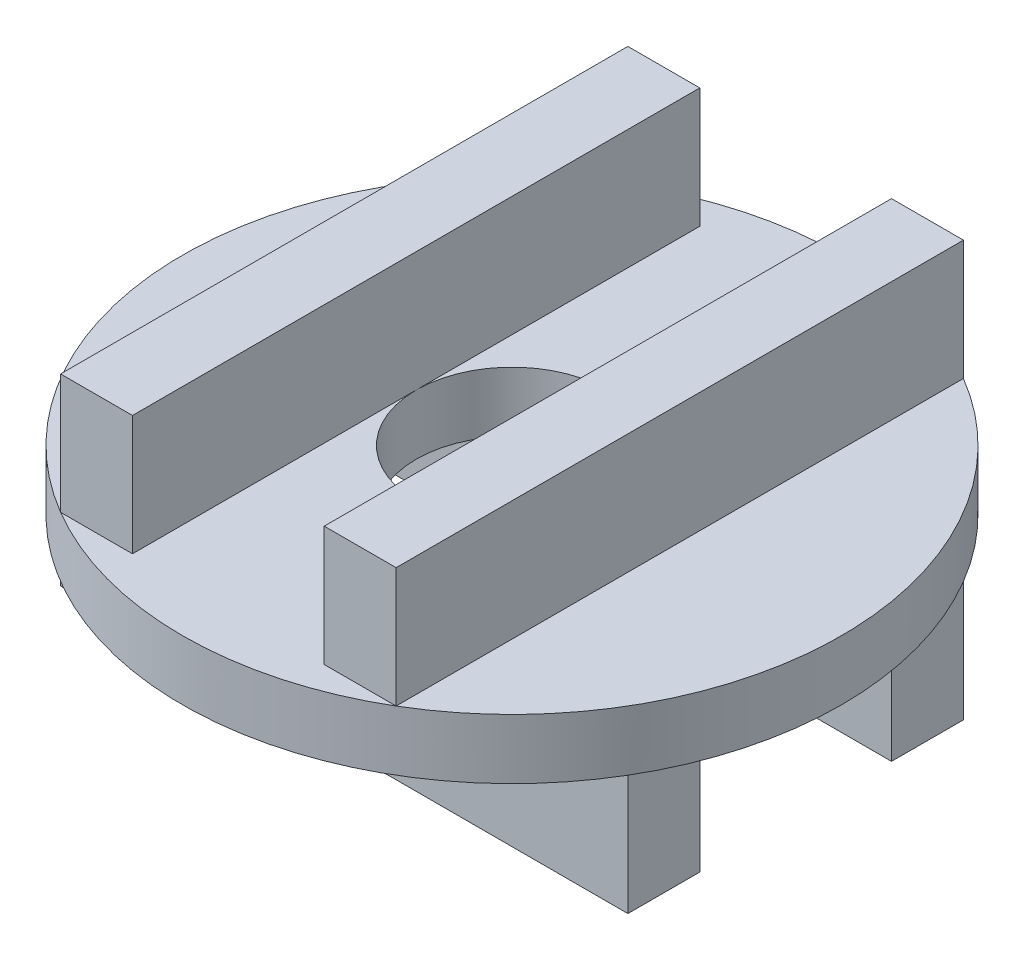
SolidWorks part; units mm, degrees
ref_plane "Front Plane" through (0, 0, 0) normal (0, 0, 1) x (1, 0, 0)
ref_plane "Top Plane" through (0, 0, 0) normal (0, 1, 0) x (1, 0, 0)
ref_plane "Right Plane" through (0, 0, 0) normal (1, 0, 0) x (0, 0, -1)
sketch "Sketch1" plane through (0, 0, 0) normal (0, 1, 0) x (1, 0, 0)
  circle A0 centre (0, 0) radius 55
  circle A1 centre (0, 0) radius 16
  dimension "D1" = 110
  dimension "D2" = 32
extrude "Boss-Extrude1" add sketch "Sketch1" along normal blind 10
sketch "Sketch2" plane through (0, 10, 0) normal (0, 1, 0) x (1, 0, 0)
  line L1 (28, 0) -> (28, 47.3392)
  line L2 (28, 47.3392) -> (16, 47.3392)
  line L3 (16, 47.3392) -> (16, 0)
  line L4 (28, 0) -> (28, -47.3392)
  line L5 (28, -47.3392) -> (16, -47.3392)
  line L6 (16, -47.3392) -> (16, 0)
  line L7 (0, 0) -> (0, 25.7998)
  line L8 (-28, -47.3392) -> (-16, -47.3392)
  line L9 (-16, -47.3392) -> (-16, 0)
  line L10 (-28, 0) -> (-28, -47.3392)
  line L11 (-28, 0) -> (-28, 47.3392)
  line L12 (-28, 47.3392) -> (-16, 47.3392)
  line L13 (-16, 47.3392) -> (-16, 0)
  circle A0 centre (0, 0) radius 16 construction
  circle A1 centre (0, 0) radius 55 construction
  dimension "D1" = 12
extrude "Boss-Extrude2" add sketch "Sketch2" along normal blind 20 contours L13 L12 L11 L10 L8 L9 | L6 L5 L4 L1 L2 L3
sketch "Sketch3" plane through (0, 0, 0) normal (0, -1, 0) x (1, 0, 0)
  line L0 (0, 16) -> (0, 28)
  line L1 (-47.3392, 28) -> (47.3392, 28)
  line L2 (47.3392, 28) -> (47.3392, 16)
  line L3 (47.3392, 16) -> (-47.3392, 16)
  line L4 (-47.3392, 28) -> (-47.3392, 16)
  line L5 (0, 0) -> (-11.0835, 0)
  line L6 (47.3392, -28) -> (47.3392, -16)
  line L7 (47.3392, -16) -> (-47.3392, -16)
  line L8 (-47.3392, -28) -> (47.3392, -28)
  line L9 (-47.3392, -28) -> (-47.3392, -16)
  circle A0 centre (0, 0) radius 16 construction
  circle A1 centre (0, 0) radius 55 construction
  dimension "D1" = 12
extrude "Boss-Extrude3" add sketch "Sketch3" along normal blind 20 contours L1 L4 L3 L0 | L3 L2 L1 L0 | A1 A0 L8 L9
